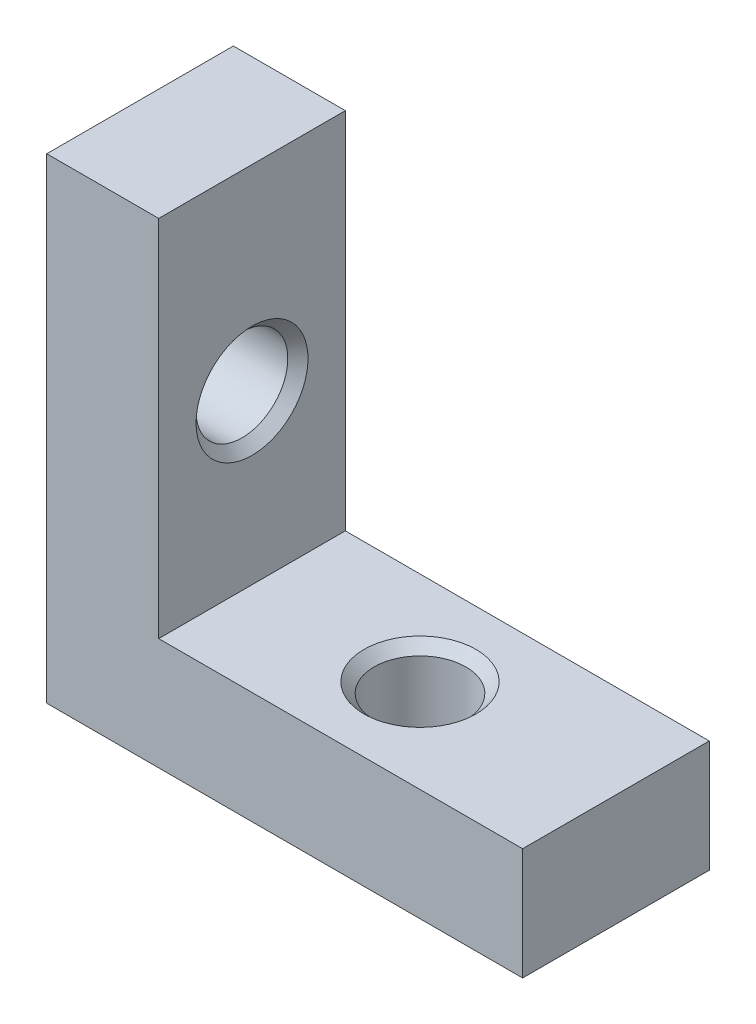
SolidWorks part; units mm, degrees
ref_plane "Plan de face" through (0, 0, 0) normal (0, 0, 1) x (1, 0, 0)
ref_plane "Plan de dessus" through (0, 0, 0) normal (0, 1, 0) x (1, 0, 0)
ref_plane "Plan de droite" through (0, 0, 0) normal (1, 0, 0) x (0, 0, -1)
ref_plane "Plan1" through (0, 0, -5) normal (0, 0, -1) x (-1, 0, 0)
sketch "Esquisse1" plane through (0, 0, -5) normal (0, 0, -1) x (-1, 0, 0)
  line L0 (-45, 0) -> (0, 0)
  line L1 (0, 0) -> (0, 45)
  line L2 (0, 45) -> (-45, 45)
  line L3 (-45, 45) -> (-45, 0)
extrude "Boss.-Extru.1" add sketch "Esquisse1" against normal blind 10
sketch "Esquisse2" plane through (0, 0, 5) normal (0, 0, 1) x (1, 0, 0)
  line L0 (45, 45) -> (6, 45)
  line L1 (6, 45) -> (6, 6)
  line L2 (6, 6) -> (45, 6)
  line L3 (45, 6) -> (45, 45)
extrude "Enlèv. mat.-Extru.1" cut sketch "Esquisse2" against normal through all
hole_wizard "Perçage1" positions "Esquisse4" profile "Esquisse3" legacy
sketch "Esquisse4" plane through (0, 6, 0) normal (0, 1, 0) x (1, 0, 0)
  point P0 (35, 0)
  point P1 (15, 0)
sketch "Esquisse3" plane through (35, 6, 0) normal (1, 0, 0) x (0, 0, 1)
  line L0 (0, 0) -> (0, 6)
  line L1 (0, 6) -> (2.4588, 6)
  line L2 (2.4588, 6) -> (2.4588, 0)
  line L3 (2.4588, 0) -> (0, 0)
  line L4 (0, 110) -> (0, -10) construction
  dimension "Diamètre" = 4.9175
  dimension "Profondeur" = 6
hole_wizard "Perçage2" positions "Esquisse6" profile "Esquisse5" legacy
sketch "Esquisse6" plane through (0, 0, 0) normal (-1, 0, 0) x (0, 0, 1)
  point P0 (0, 15)
sketch "Esquisse5" plane through (0, 15, 0) normal (0, 1, 0) x (0, 0, 1)
  line L0 (0, 0) -> (0, 45)
  line L1 (0, 45) -> (2.4588, 45)
  line L2 (2.4588, 45) -> (2.4588, 0)
  line L3 (2.4588, 0) -> (0, 0)
  line L4 (0, 110) -> (0, -10) construction
  dimension "Diamètre" = 4.9175
  dimension "Profondeur" = 45
hole_wizard "Perçage3" positions "Esquisse8" profile "Esquisse7" legacy
sketch "Esquisse8" plane through (6, 0, 0) normal (1, 0, 0) x (0, 0, -1)
  point P0 (0, 35)
sketch "Esquisse7" plane through (6, 35, 0) normal (0, 1, 0) x (0, 0, -1)
  line L0 (0, 0) -> (0, 6)
  line L1 (0, 6) -> (2.4588, 6)
  line L2 (2.4588, 6) -> (2.4588, 0)
  line L3 (2.4588, 0) -> (0, 0)
  line L4 (0, 110) -> (0, -10) construction
  dimension "Diamètre" = 4.9175
  dimension "Profondeur" = 6
chamfer "Chanfrein1" distance 0.5412 angle 45 8 edges at (15, 0, 2.4588) (35, 0, 2.4588) (35, 6, 2.4588) (0, 35, -2.4588) (15, 6, 2.4588) (6, 15, 2.4588) (6, 35, -2.4588) (0, 15, 2.4588)
sketch "Esquisse9" plane through (0, 6, 0) normal (0, 1, 0) x (1, 0, 0)
  line L0 (25.5, 5) -> (25.5, -5)
  line L1 (6, 5) -> (45, 5) construction
  line L2 (6, -5) -> (45, -5) construction
  line L7 (6, -5) -> (45, -5)
  line L8 (45, -5) -> (45, 5)
  line L9 (45, 5) -> (6, 5)
  line L10 (6, 5) -> (6, -5)
  line L11 (25.5, -5) -> (45, -5)
  line L12 (45, -5) -> (45, 5)
  line L13 (45, 5) -> (25.5, 5)
  dimension "D1" = 0
extrude "Enlèv. mat.-Extru.2" cut sketch "Esquisse9" against normal blind 10
sketch "Esquisse10" plane through (6, 0, 0) normal (1, 0, 0) x (0, 0, -1)
  line L0 (-5, 25.5) -> (5, 25.5)
  line L1 (-5, 45) -> (-5, 6) construction
  line L2 (5, 45) -> (5, 6) construction
  line L7 (-5, 45) -> (-5, 6)
  line L8 (-5, 6) -> (5, 6)
  line L9 (5, 6) -> (5, 45)
  line L10 (5, 45) -> (-5, 45)
  line L11 (-5, 45) -> (-5, 25.5)
  line L13 (5, 25.5) -> (5, 45)
  line L14 (5, 45) -> (-5, 45)
  dimension "D1" = 0
extrude "Enlèv. mat.-Extru.3" cut sketch "Esquisse10" against normal blind 10
